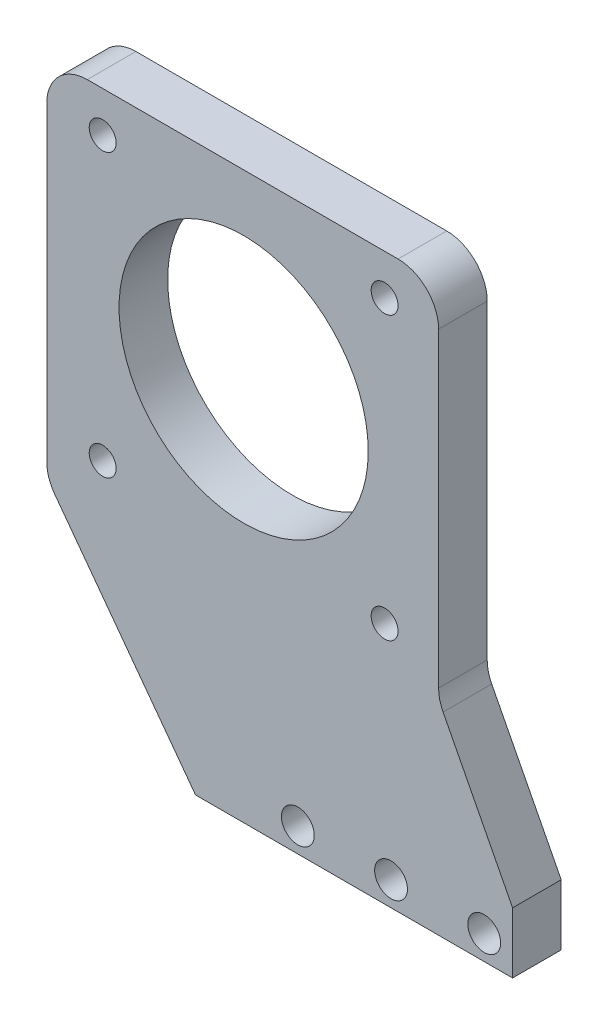
SolidWorks part; units mm, degrees
material "AISI Type 316L stainless steel"
ref_plane "Front Plane" through (0, 0, 0) normal (0, 0, 1) x (1, 0, 0)
ref_plane "Top Plane" through (0, 0, 0) normal (0, 1, 0) x (1, 0, 0)
ref_plane "Right Plane" through (0, 0, 0) normal (1, 0, 0) x (0, 0, -1)
sketch "Sketch1" plane through (0, 0, 0) normal (0, 0, 1) x (1, 0, 0)
  line L6 (-34.7486, 46.8937) -> (0, 0)
  line L8 (59.9847, 52.8474) -> (59.9847, 129.5461)
  line L9 (49.9847, 139.5461) -> (-26.714, 139.5461)
  line L10 (-36.714, 52.8474) -> (-36.714, 129.5461)
  line L11 (59.9847, 50.421) -> (-36.714, 139.5461) construction
  line L12 (59.9847, 139.5461) -> (-36.714, 49.5461) construction
  line L13 (0, 0) -> (78.249, 0)
  line L14 (78.249, 0) -> (78.249, 15)
  line L15 (78.249, 15) -> (61.0967, 48.2644)
  line L17 (46.6615, 59.9759) -> (-22.9185, 59.9759) construction
  line L18 (46.6615, 59.9759) -> (46.6615, 129.5559) construction
  line L19 (46.6615, 129.5559) -> (-22.9185, 129.5559) construction
  line L20 (-22.9185, 59.9759) -> (-22.9185, 129.5559) construction
  line L21 (46.6615, 59.9759) -> (-22.9185, 129.5559) construction
  line L22 (46.6615, 129.5559) -> (-22.9185, 59.9759) construction
  circle A1 centre (11.8715, 94.7659) radius 30.75
  circle A3 centre (46.6615, 129.5559) radius 3.325
  circle A4 centre (46.6615, 59.9759) radius 3.325
  circle A5 centre (-22.9185, 59.9759) radius 3.325
  arc A6 (61.0967, 48.2644) -> (59.9847, 52.8474) centre (69.9847, 52.8474) cw
  arc A7 (-34.7486, 46.8937) -> (-36.714, 52.8474) centre (-26.714, 52.8474) cw
  arc A8 (59.9847, 129.5461) -> (49.9847, 139.5461) centre (49.9847, 129.5461) ccw
  arc A9 (-26.714, 139.5461) -> (-36.714, 129.5461) centre (-26.714, 129.5461) ccw
  circle A10 centre (-22.9185, 129.5559) radius 3.325
  dimension "D8" = 61.5
  dimension "D9" = 6.65
  dimension "D5" = 90
  dimension "D10" = 69.58
  dimension "D14" = 10
  dimension "D15" = 3.325
  dimension "D2" = 66.3775
  dimension "D7" = 94.7659
  dimension "D11" = 78.249
  dimension "D12" = 15
  dimension "D16" = 96.7027
extrude "Boss-Extrude1" add sketch "Sketch1" along normal mid plane 12
sketch "Sketch2" plane through (0, 0, 6) normal (0, 0, 1) x (1, 0, 0)
  line L2 (0, 0) -> (78.249, 0) construction
  line L3 (78.249, 0) -> (78.249, 15) construction
  circle A1 centre (71.249, 6) radius 4.05
  dimension "D4" = 8.1
  dimension "D5" = 6
  dimension "D6" = 7
extrude "Cut-Extrude1" cut sketch "Sketch2" against normal through all
pattern_linear "LPattern1" count 3 spacing 23 along (-1, 0, 0) of "Cut-Extrude1"
